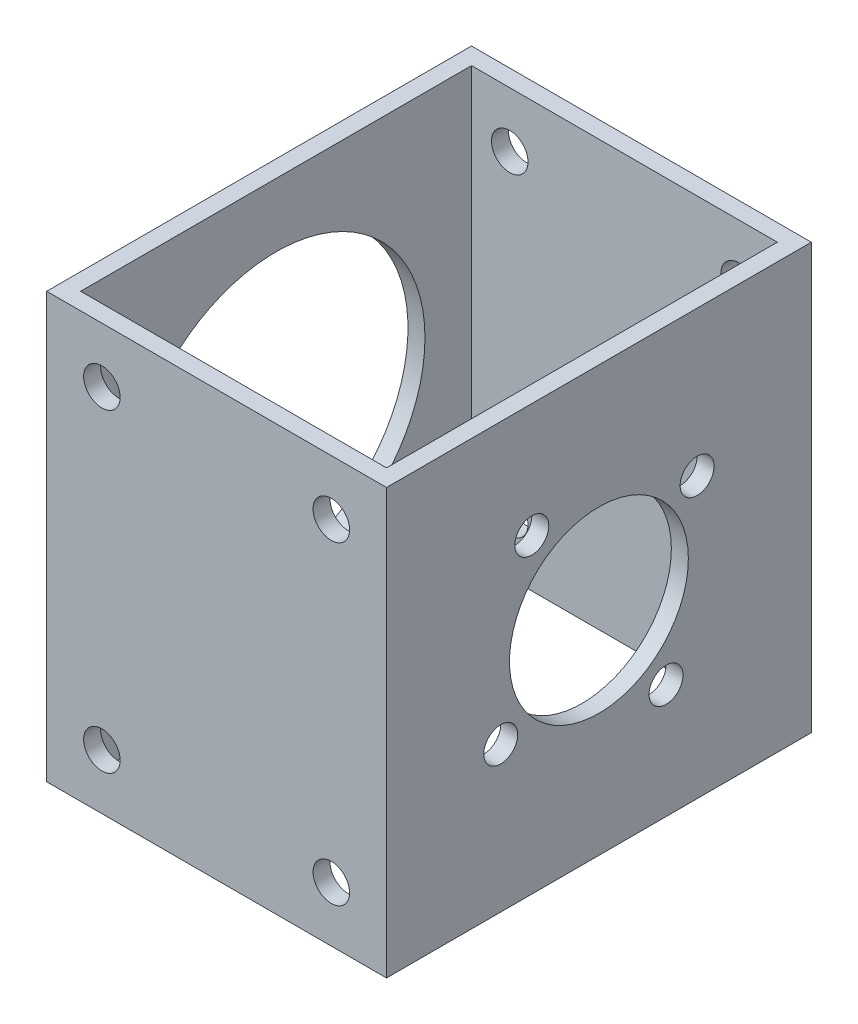
SolidWorks part; units mm, degrees
material "1060 合金"
ref_plane "前视基准面" through (0, 0, 0) normal (0, 0, 1) x (1, 0, 0)
ref_plane "上视基准面" through (0, 0, 0) normal (0, 1, 0) x (1, 0, 0)
ref_plane "右视基准面" through (0, 0, 0) normal (1, 0, 0) x (0, 0, -1)
other "电机1号"
sketch "草图1" plane through (0, 0, 0) normal (0, 1, 0) x (1, 0, 0)
  line L0 (2, -2) -> (38, -2)
  line L1 (0, 0) -> (40, 0)
  line L2 (0, 0) -> (0, -50)
  line L3 (0, -50) -> (40, -50)
  line L4 (40, 0) -> (40, -50)
  line L5 (38, -2) -> (38, -48)
  line L6 (2, -48) -> (38, -48)
  line L7 (2, -2) -> (2, -48)
  dimension "D1" = 40
  dimension "D2" = 50
  dimension "D3" = 2
extrude "凸台-拉伸1" add sketch "草图1" along normal blind 50
sketch "草图2" plane through (0, 0, 0) normal (0, 0, -1) x (-1, 0, 0)
  line L0 (0, 50) -> (0, 0) construction
  line L1 (-40, 0) -> (0, 0) construction
  line L2 (-40, 50) -> (-40, 0) construction
  line L3 (-40, 50) -> (0, 50) construction
  circle A0 centre (-6.5, 6.5) radius 2.15
  circle A1 centre (-33.5, 6.5) radius 2.15
  circle A2 centre (-33.5, 43.5) radius 2.15
  circle A3 centre (-6.5, 43.5) radius 2.15
  dimension "D1" = 4.3
  dimension "D2" = 6.5
  dimension "D4" = 6.5
  dimension "D8" = 6.5
  dimension "D3" = 6.5
  dimension "D5" = 6.5
  dimension "D6" = 6.5
  dimension "D7" = 6.5
  dimension "D9" = 6.5
extrude "切除-拉伸1" cut sketch "草图2" against normal through all
sketch "草图3" plane through (0, 0, 0) normal (-1, 0, 0) x (0, 0, 1)
  line L0 (0, 50) -> (0, 0) construction
  line L3 (0, 50) -> (50, 50) construction
  circle A0 centre (25, 25) radius 17.525
  dimension "D1" = 35.05
  dimension "D2" = 25
  dimension "D3" = 25
extrude "切除-拉伸2" cut sketch "草图3" against normal up to next
sketch "草图4" plane through (40, 0, 0) normal (1, 0, 0) x (0, 0, -1)
  line L0 (0, 50) -> (0, 0) construction
  line L1 (-50, 0) -> (0, 0) construction
  line L2 (-25, 25) -> (0, 25) construction
  circle A0 centre (-25, 25) radius 10.525
  point P27 (-25, 25)
  dimension "D1" = 21.05
  dimension "D2" = 25
  dimension "D3" = 25
extrude "切除-拉伸3" cut sketch "草图4" against normal up to next
sketch "草图5" plane through (40, 0, 0) normal (1, 0, 0) x (0, 0, -1)
  line L0 (-50, 7.4) -> (0, 7.4) construction
  line L2 (0, 50) -> (0, 0) construction
  circle A0 centre (-17.1, 13.4419) radius 2
  circle A1 centre (-25, 25) radius 10.525 construction
  circle A2 centre (-36.5581, 17.1) radius 2
  circle A3 centre (-32.9, 36.5581) radius 2
  circle A4 centre (-13.4419, 32.9) radius 2
  circle A5 centre (-25, 25) radius 17.6 construction
  point P13 (-25, 25)
  point P19 (-25, 7.4)
  dimension "D1" = 4
  dimension "D4" = 35.2
  dimension "D2" = 14
  dimension "D5" = 25.5
  dimension "D3" = 4
extrude "切除-拉伸5" cut sketch "草图5" against normal blind 10
sketch "草图7" plane through (40, 0, 0) normal (1, 0, 0) x (0, 0, -1)
  line L0 (-50, 7.4) -> (0, 7.4) construction
  line L1 (0, 50) -> (0, 0) construction
  circle A0 centre (-25, 25) radius 17.6 construction
  circle A1 centre (-14.1931, 33.9) radius 2
  circle A2 centre (-16.1, 14.1931) radius 2
  circle A3 centre (-35.8069, 16.1) radius 2
  circle A4 centre (-33.9, 35.8069) radius 2
  point P10 (-25, 7.4)
  point P19 (-25, 25)
  dimension "D1" = 35.2
  dimension "D2" = 4
  dimension "D3" = 14
  dimension "D5" = 26.5
  dimension "D4" = 4
extrude "电机2号" [suppressed] cut sketch "草图7" against normal blind 10
sketch "草图8" plane through (40, 0, 0) normal (1, 0, 0) x (0, 0, -1)
  line L0 (-50, 7.4) -> (0, 7.4) construction
  circle A0 centre (-25, 25) radius 17.6 construction
  circle A1 centre (-13.8, 33.4) radius 2
  circle A2 centre (-16.6, 13.8) radius 2
  circle A3 centre (-36.2, 16.6) radius 2
  circle A4 centre (-33.4, 36.2) radius 2
  point P8 (-25, 7.4)
  point P17 (-25, 25)
  dimension "D1" = 35.2
  dimension "D2" = 4
  dimension "D5" = 26
  dimension "D3" = 14
  dimension "D4" = 4
extrude "电机3号" [suppressed] cut sketch "草图8" against normal blind 10
sketch "草图9" plane through (40, 0, 0) normal (1, 0, 0) x (0, 0, -1)
  line L0 (-50, 7.4) -> (0, 7.4) construction
  line L1 (0, 50) -> (0, 0) construction
  circle A0 centre (-25, 25) radius 17.6 construction
  circle A1 centre (-11.0004, 24.9) radius 2
  circle A2 centre (-25.1, 11.0004) radius 2
  circle A3 centre (-38.9996, 25.1) radius 2
  circle A4 centre (-24.9, 38.9996) radius 2
  point P10 (-25, 7.4)
  point P19 (-25, 25)
  dimension "D1" = 4
  dimension "D2" = 35.2
  dimension "D3" = 14
  dimension "D5" = 17.5
  dimension "D4" = 4
extrude "电机4号" [suppressed] cut sketch "草图9" against normal blind 10
sketch "草图10" plane through (40, 0, 0) normal (1, 0, 0) x (0, 0, -1)
  line L0 (-50, 7.4) -> (0, 7.4) construction
  circle A0 centre (-25, 25) radius 17.6 construction
  circle A1 centre (-11.029, 25.9) radius 2
  circle A2 centre (-24.1, 11.029) radius 2
  circle A3 centre (-38.971, 24.1) radius 2
  circle A4 centre (-25.9, 38.971) radius 2
  point P8 (-25, 7.4)
  point P17 (-25, 25)
  dimension "D1" = 35.2
  dimension "D2" = 4
  dimension "D3" = 14
  dimension "D5" = 18.5
  dimension "D4" = 4
extrude "电机5号" [suppressed] cut sketch "草图10" against normal blind 10
sketch "草图11" plane through (40, 0, 0) normal (1, 0, 0) x (0, 0, -1)
  line L0 (-50, 7.4) -> (0, 7.4) construction
  line L1 (0, 50) -> (0, 0) construction
  circle A0 centre (-25, 25) radius 17.6 construction
  circle A1 centre (-17.4, 36.7576) radius 2
  circle A2 centre (-13.2424, 17.4) radius 2
  circle A3 centre (-32.6, 13.2424) radius 2
  circle A4 centre (-36.7576, 32.6) radius 2
  point P10 (-25, 7.4)
  point P19 (-25, 25)
  dimension "D1" = 35.2
  dimension "D2" = 4
  dimension "D3" = 14
  dimension "D5" = 10
  dimension "D4" = 4
extrude "电机6号" [suppressed] cut sketch "草图11" against normal blind 10
sketch "草图12" plane through (40, 0, 0) normal (1, 0, 0) x (0, 0, -1)
  line L0 (-50, 7.4) -> (0, 7.4) construction
  line L1 (0, 50) -> (0, 0) construction
  circle A0 centre (-25, 25) radius 17.6 construction
  circle A1 centre (-12.3039, 30.9) radius 2
  circle A2 centre (-19.1, 12.3039) radius 2
  circle A3 centre (-37.6961, 19.1) radius 2
  circle A4 centre (-30.9, 37.6961) radius 2
  point P10 (-25, 7.4)
  point P19 (-25, 25)
  dimension "D1" = 4
  dimension "D2" = 35.2
  dimension "D3" = 14
  dimension "D5" = 23.5
  dimension "D4" = 4
extrude "电机7号" [suppressed] cut sketch "草图12" against normal blind 10
